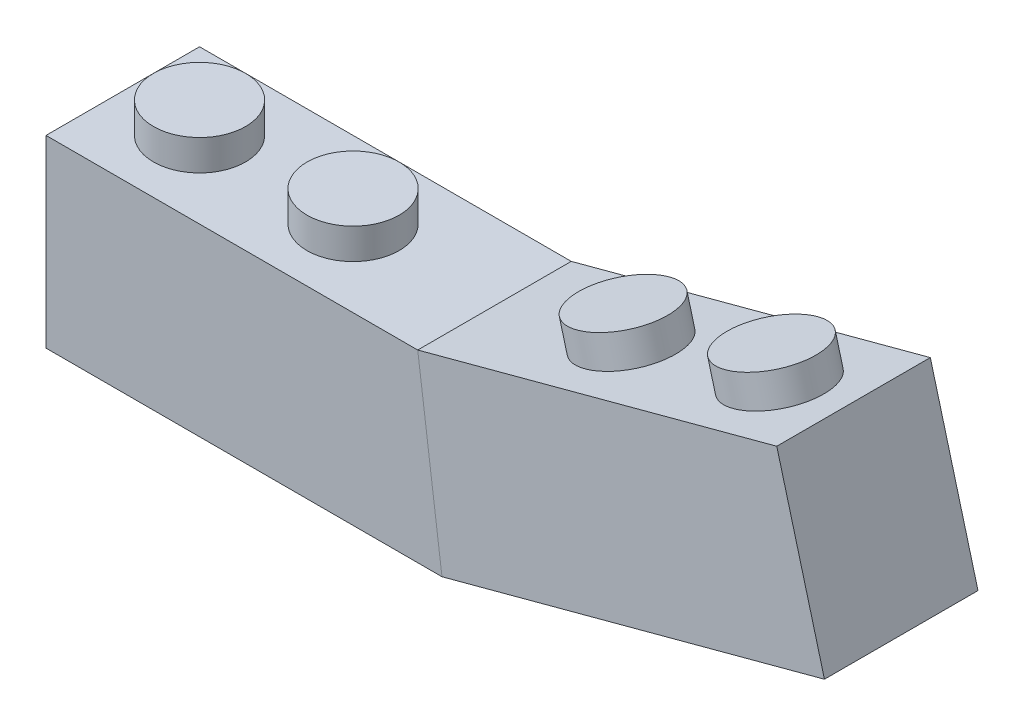
SolidWorks part; units mm, degrees
ref_plane "Front Plane" through (0, 0, 0) normal (0, 0, 1) x (1, 0, 0)
ref_plane "Top Plane" through (0, 0, 0) normal (0, 1, 0) x (1, 0, 0)
ref_plane "Right Plane" through (0, 0, 0) normal (1, 0, 0) x (0, 0, -1)
sketch "Sketch2" plane through (0, 0, 0) normal (1, 0, 0) x (0, 0, -1)
  line L1 (-4, -4.8) -> (4, -4.8)
  line L2 (-4, -4.8) -> (-4, 4.8)
  line L3 (-4, 4.8) -> (4, 4.8)
  line L4 (4, -4.8) -> (4, 4.8)
  line L5 (-4, -4.8) -> (4, 4.8) construction
  line L6 (-4, 4.8) -> (4, -4.8) construction
  point P0 (0, 0)
  dimension "D1" = 9.6
  dimension "D2" = 8
sketch "Sketch3" plane through (0, 0, 0) normal (0, 0, 1) x (1, 0, 0)
  line L0 (0, 0) -> (20, 0)
  line L1 (20, 0) -> (39.3185, 5.1764)
  dimension "D1" = 20
  dimension "D2" = 20
  dimension "D3" = 195
sweep "Sweep1" add profiles "Sketch2" path "Sketch3"
sketch "Sketch4" plane through (0, 4.8, 0) normal (0, 1, 0) x (1, 0, 0)
  line L0 (0, 0) -> (4, 0) construction
  circle A0 centre (4, 0) radius 2.4
  dimension "D2" = 4.8
  dimension "D1" = 4
extrude "Boss-Extrude1" add sketch "Sketch4" along normal blind 1.6
pattern_linear "LPattern1" count 2 spacing 8 along (1, 0, 0) of "Boss-Extrude1"
sketch "Sketch5" plane through (0.0974, -0.3636, 0) normal (-0.2588, 0.9659, 0) x (0.9659, 0.2588, 0)
  line L0 (39.3185, 0) -> (35.3185, 0) construction
  line L1 (39.3185, 4) -> (39.3185, -4) construction
  circle A0 centre (35.3185, 0) radius 2.4
  dimension "D2" = 4.8
  dimension "D1" = 4
extrude "Boss-Extrude2" add sketch "Sketch5" along normal blind 1.6
pattern_linear "LPattern2" count 2 spacing 8 along (-0.9659, -0.2588, 0) of "Boss-Extrude2"
shell "Shell1" thickness 1.6
